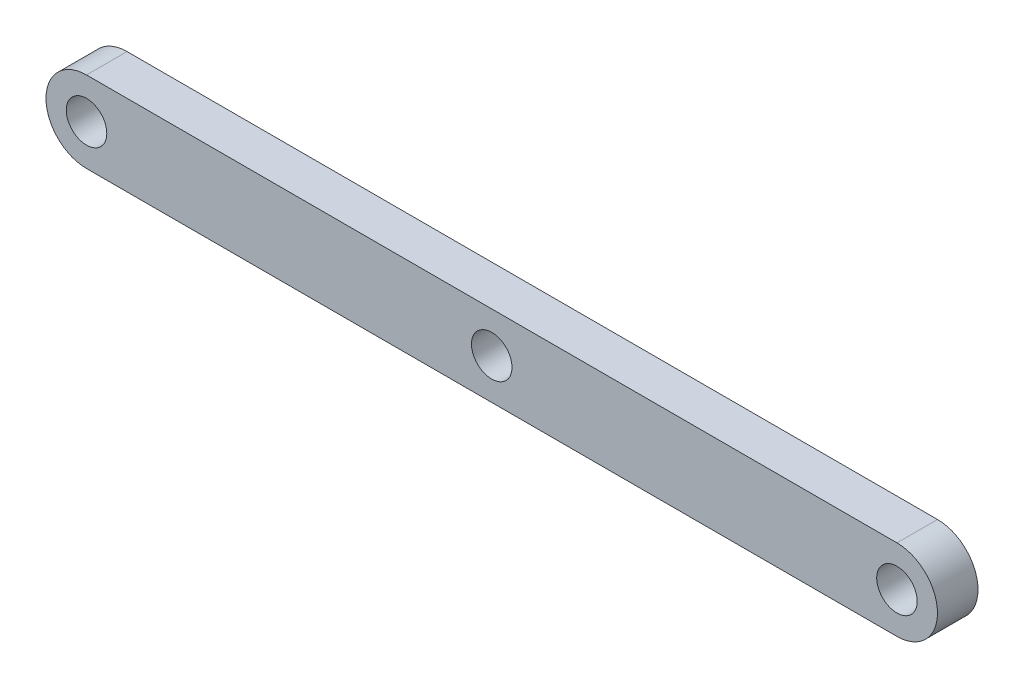
SolidWorks part; units mm, degrees
ref_plane "前基準面" through (0, 0, 0) normal (0, 0, 1) x (1, 0, 0)
ref_plane "上基準面" through (0, 0, 0) normal (0, 1, 0) x (1, 0, 0)
ref_plane "右基準面" through (0, 0, 0) normal (1, 0, 0) x (0, 0, -1)
sketch "草圖1" plane through (0, 0, 0) normal (0, 0, 1) x (1, 0, 0)
  line L0 (-20, 2.001) -> (20, 2.001)
  line L1 (-20, -1.999) -> (20, -1.999)
  arc A0 (-20, 2.001) -> (-20, -1.999) centre (-20, 0.001) ccw
  arc A1 (20, -1.999) -> (20, 2.001) centre (20, 0.001) ccw
  circle A2 centre (-20, 0.001) radius 1
  circle A3 centre (20, 0.001) radius 1
  circle A4 centre (0, 0) radius 1
  dimension "D1" = 40
  dimension "D2" = 2
  dimension "D3" = 2
  dimension "D4" = 2
  dimension "D5" = 20
  dimension "D6" = 2
extrude "填料-伸長1" add sketch "草圖1" along normal blind 2
